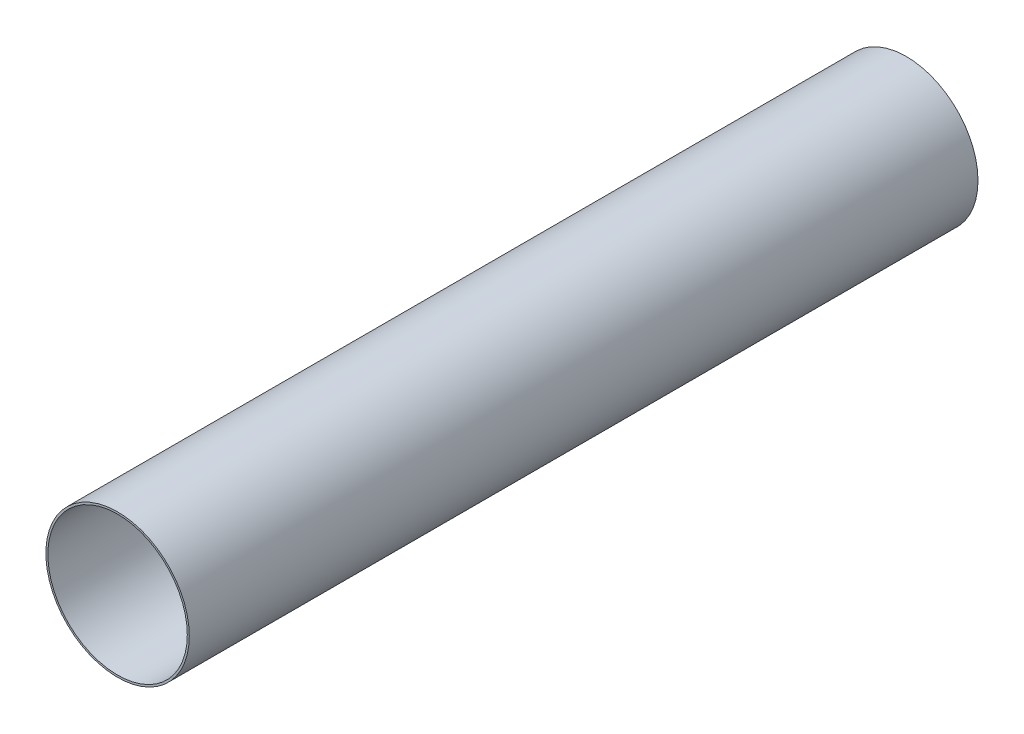
SolidWorks part; units mm, degrees
ref_plane "Plan de face" through (0, 0, 0) normal (0, 0, 1) x (1, 0, 0)
ref_plane "Plan de dessus" through (0, 0, 0) normal (0, 1, 0) x (1, 0, 0)
ref_plane "Plan de droite" through (0, 0, 0) normal (1, 0, 0) x (0, 0, -1)
sketch "Esquisse1" plane through (0, 0, 0) normal (0, 0, 1) x (1, 0, 0)
  circle A0 centre (0, 0) radius 50.8
  circle A1 centre (0, 0) radius 49.403
  dimension "D1" = 101.6
  dimension "D2" = 98.806
extrude "Boss.-Extru.1" add sketch "Esquisse1" along normal blind 558.8
